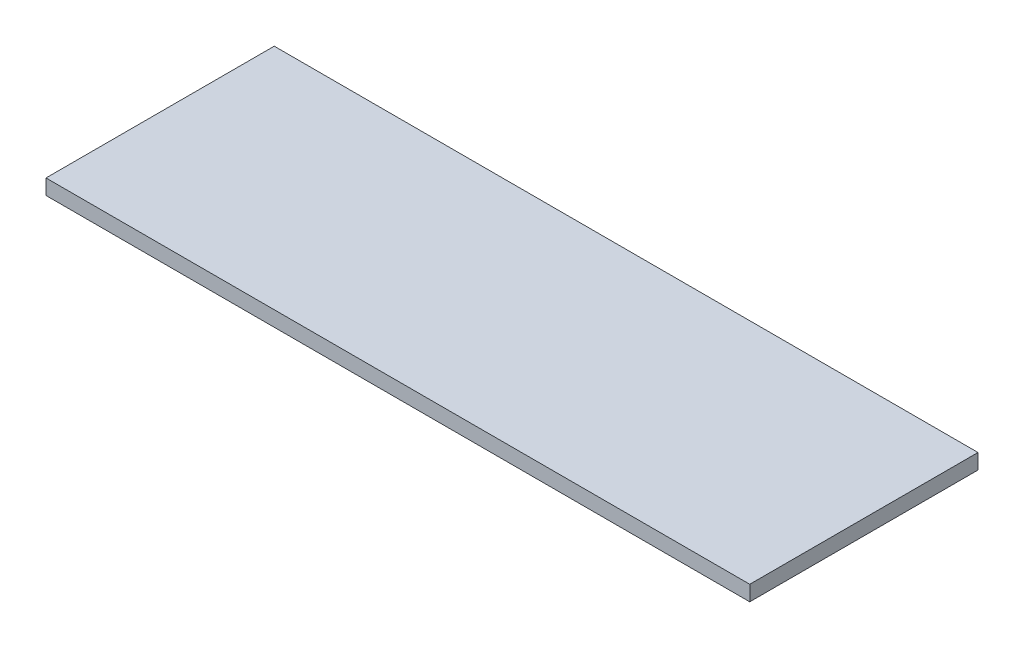
SolidWorks part; units mm, degrees
ref_plane "Front Plane" through (0, 0, 0) normal (0, 0, 1) x (1, 0, 0)
ref_plane "Top Plane" through (0, 0, 0) normal (0, 1, 0) x (1, 0, 0)
ref_plane "Right Plane" through (0, 0, 0) normal (1, 0, 0) x (0, 0, -1)
sketch "Sketch1" plane through (0, 0, 0) normal (0, 1, 0) x (1, 0, 0)
  line L1 (0, 0) -> (74, 0)
  line L2 (0, 0) -> (0, 24)
  line L3 (0, 24) -> (74, 24)
  line L4 (74, 0) -> (74, 24)
  dimension "D1" = 24
  dimension "D2" = 74
extrude "Boss-Extrude1" add sketch "Sketch1" along normal blind 1.6
